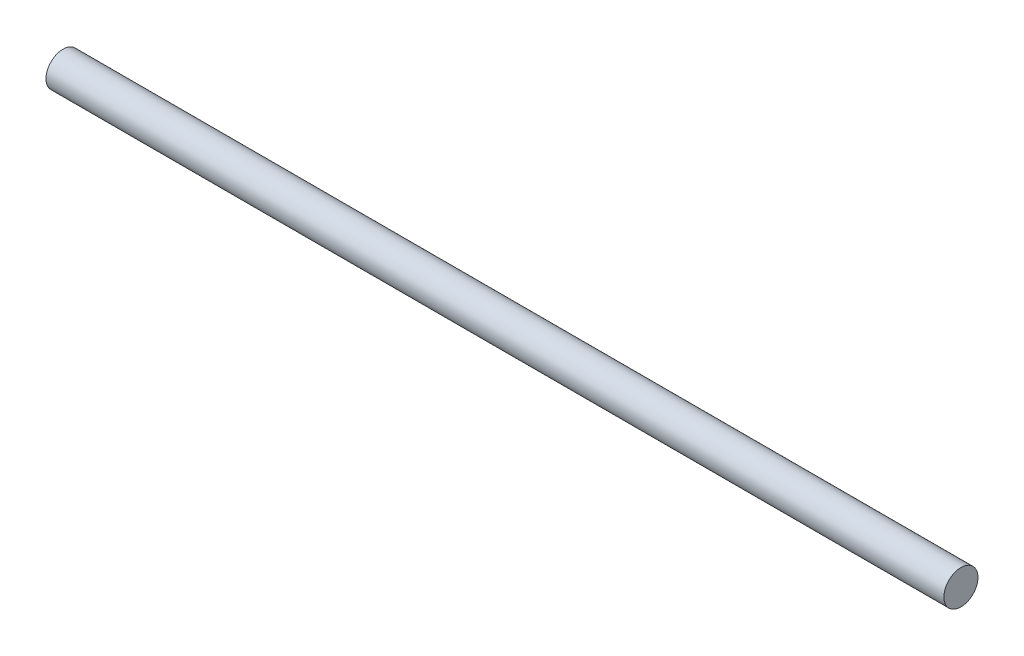
SolidWorks part; units mm, degrees
material "AISI 304"
ref_plane "Front Plane" through (0, 0, 0) normal (0, 0, 1) x (1, 0, 0)
ref_plane "Top Plane" through (0, 0, 0) normal (0, 1, 0) x (1, 0, 0)
ref_plane "Right Plane" through (0, 0, 0) normal (1, 0, 0) x (0, 0, -1)
sketch "Sketch1" plane through (0, 0, 0) normal (1, 0, 0) x (0, 0, -1)
  circle A0 centre (0, 0) radius 19
  dimension "D1" = 38
extrude "Boss-Extrude1" add sketch "Sketch1" along normal blind 1000 contours A0
